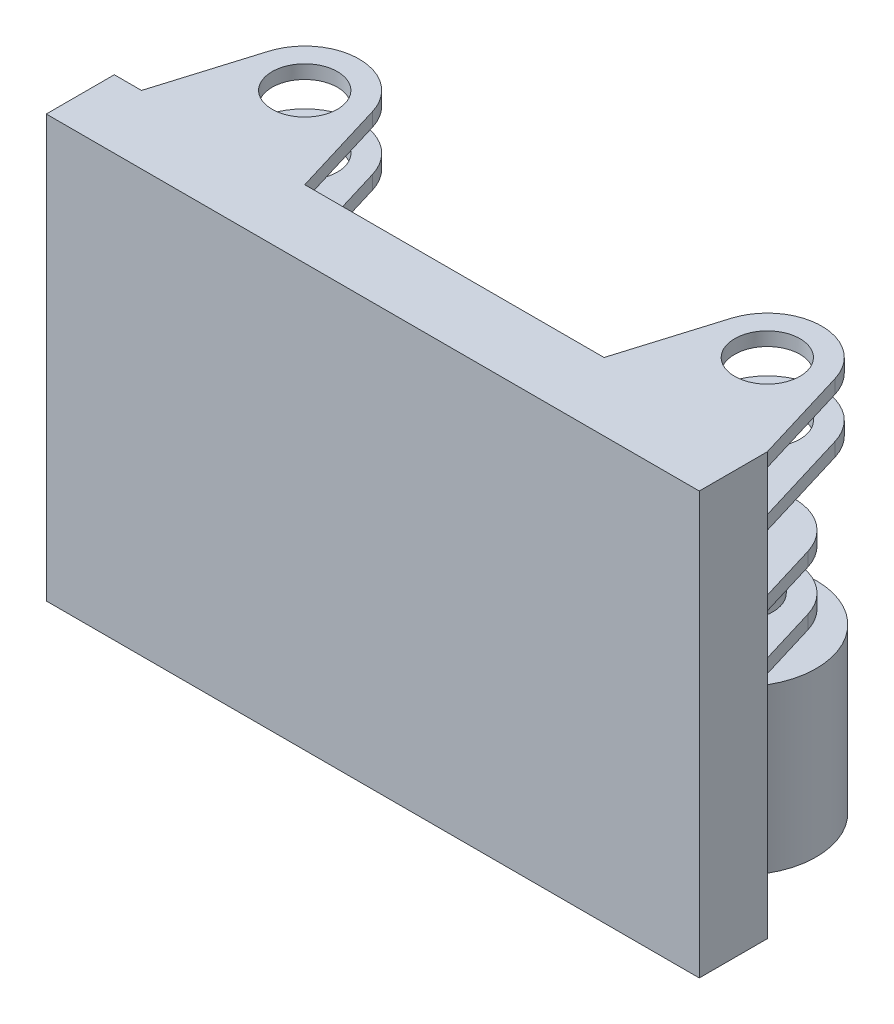
SolidWorks part; units mm, degrees
ref_plane "前视基准面" through (0, 0, 0) normal (0, 0, 1) x (1, 0, 0)
ref_plane "上视基准面" through (0, 0, 0) normal (0, 1, 0) x (1, 0, 0)
ref_plane "右视基准面" through (0, 0, 0) normal (1, 0, 0) x (0, 0, -1)
sketch "草图1" plane through (0, 0, 0) normal (0, 0, 1) x (1, 0, 0)
  line L1 (0, 0) -> (240, 0)
  line L2 (0, 0) -> (0, 85)
  line L3 (0, 85) -> (240, 85)
  line L4 (240, 0) -> (240, 85)
extrude "凸台-拉伸1" add sketch "草图1" along normal blind 25
sketch "草图2" plane through (0, 0, 0) normal (0, -1, 0) x (1, 0, 0)
  line L0 (0, 0) -> (30, 0)
  line L1 (0, 0) -> (240, 0) construction
  line L2 (170, 0) -> (230, 0)
  line L3 (30, 0) -> (60, 0)
  line L4 (0, 0) -> (10.8611, -35.8055)
  line L5 (60, 0) -> (49.1389, -35.8055)
  line L6 (170, 0) -> (180.8611, -35.8055)
  line L7 (230, 0) -> (219.1389, -35.8055)
  circle A0 centre (30, -30) radius 12
  arc A1 (10.8611, -35.8055) -> (49.1389, -35.8055) centre (30, -30) ccw
  circle A2 centre (200, -30) radius 12
  arc A3 (180.8611, -35.8055) -> (219.1389, -35.8055) centre (200, -30) ccw
extrude "凸台-拉伸2" add sketch "草图2" against normal blind 25
ref_plane "基准面4" through (0, 5, 0) normal (0, -1, 0) x (-1, 0, 0)
sketch "草图3" plane through (0, 5, 0) normal (0, -1, 0) x (-1, 0, 0)
  line L1 (-230, 0) -> (3.3375, 0)
  line L2 (-230, 0) -> (-230, 53.7002)
  line L3 (-230, 53.7002) -> (3.3375, 53.7002)
  line L4 (3.3375, 0) -> (3.3375, 53.7002)
extrude "切除-拉伸1" cut sketch "草图3" against normal blind 15
sketch "草图4" plane through (0, 85, 0) normal (0, 1, 0) x (1, 0, 0)
  line L0 (20.8611, 35.8055) -> (10, 0)
  line L1 (10, 0) -> (70, 0)
  line L2 (70, 0) -> (59.1389, 35.8055)
  line L3 (190.8611, 35.8055) -> (180, 0)
  line L5 (180, 0) -> (240, 0)
  line L7 (240, 0) -> (229.1389, 35.8055)
  circle A0 centre (40, 30) radius 12
  arc A1 (59.1389, 35.8055) -> (20.8611, 35.8055) centre (40, 30) ccw
  circle A2 centre (210, 30) radius 12
  arc A3 (229.1389, 35.8055) -> (190.8611, 35.8055) centre (210, 30) ccw
extrude "凸台-拉伸3" add sketch "草图4" against normal blind 25
ref_plane "基准面5" through (0, 80, 0) normal (0, 1, 0) x (1, 0, 0)
sketch "草图5" plane through (0, 80, 0) normal (0, 1, 0) x (1, 0, 0)
  line L1 (10, 0) -> (250.1318, 0)
  line L2 (10, 0) -> (10, 54.0029)
  line L3 (10, 54.0029) -> (250.1318, 54.0029)
  line L4 (250.1318, 0) -> (250.1318, 54.0029)
extrude "切除-拉伸2" cut sketch "草图5" against normal blind 15
sketch "草图6" plane through (0, 0, 0) normal (0, -1, 0) x (1, 0, 0)
  circle A1 centre (200, -30) radius 12
extrude "凸台-拉伸4" add sketch "草图6" against normal blind 25 and the other way blind 5
sketch "草图8" plane through (0, -5, 0) normal (0, -1, 0) x (1, 0, 0)
  circle A7 centre (200, -30) radius 28
extrude "凸台-拉伸5" add sketch "草图8" along normal blind 60
sketch "草图9" plane through (0, 0, 0) normal (0, -1, 0) x (1, 0, 0)
  line L1 (0, 0) -> (240, 0)
  line L2 (0, 0) -> (0, 25)
  line L3 (0, 25) -> (240, 25)
  line L4 (240, 0) -> (240, 25)
extrude "凸台-拉伸6" add sketch "草图9" along normal blind 70
sketch "草图10" plane through (0, 0, 0) normal (0, 0, -1) x (-1, 0, 0)
  line L3 (-218, -15) -> (-218, -55)
  line L6 (-182, -15) -> (-182, -55)
  line L7 (-218, -55) -> (-182, -55)
  line L8 (-218, -15) -> (-182, -15)
extrude "凸台-拉伸7" add sketch "草图10" along normal blind 15
sketch "草图11" plane through (0, -70, 0) normal (0, -1, 0) x (1, 0, 0)
  circle A0 centre (50, 12.5) radius 10
  circle A1 centre (190, 12.5) radius 10
extrude "切除-拉伸3" cut sketch "草图11" against normal blind 10
